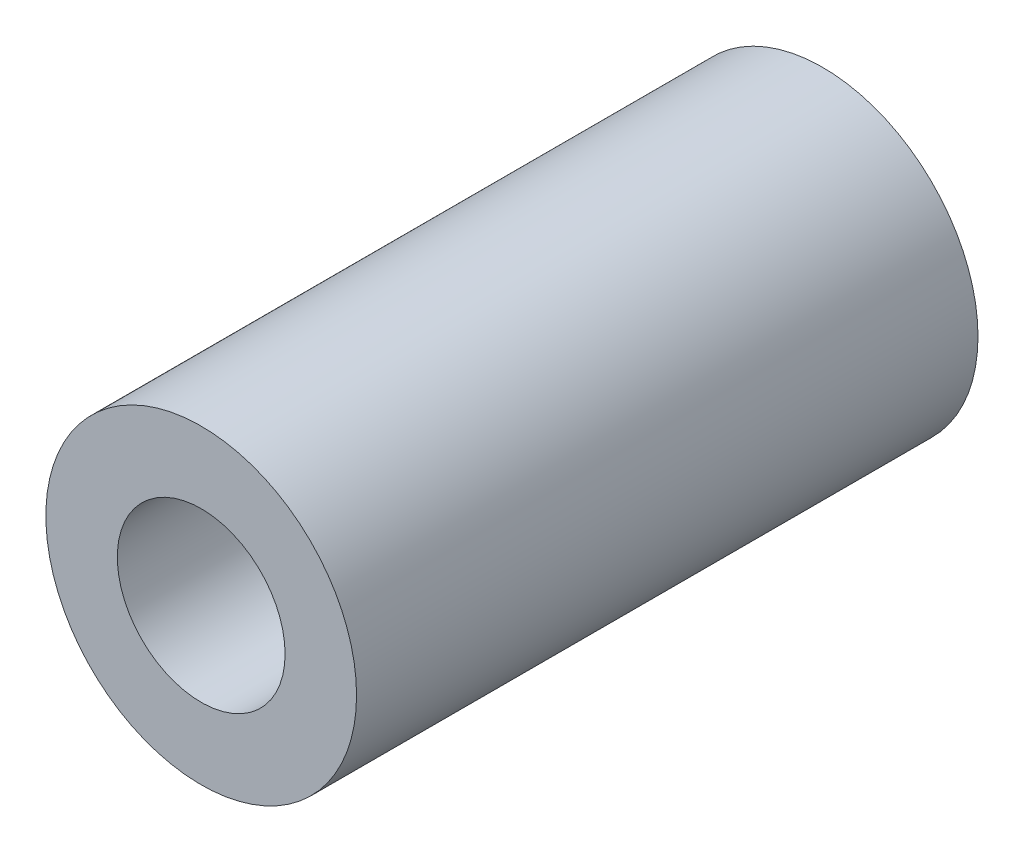
SolidWorks part; units mm, degrees
ref_plane "Front Plane" through (0, 0, 0) normal (0, 0, 1) x (1, 0, 0)
ref_plane "Top Plane" through (0, 0, 0) normal (0, 1, 0) x (1, 0, 0)
ref_plane "Right Plane" through (0, 0, 0) normal (1, 0, 0) x (0, 0, -1)
sketch "Sketch1" plane through (0, 0, 0) normal (0, 0, 1) x (1, 0, 0)
  circle A0 centre (0, 0) radius 1.35
  circle A1 centre (0, 0) radius 2.5
  dimension "D1" = 2.7
  dimension "D2" = 5
extrude "Boss-Extrude1" add sketch "Sketch1" along normal blind 10
